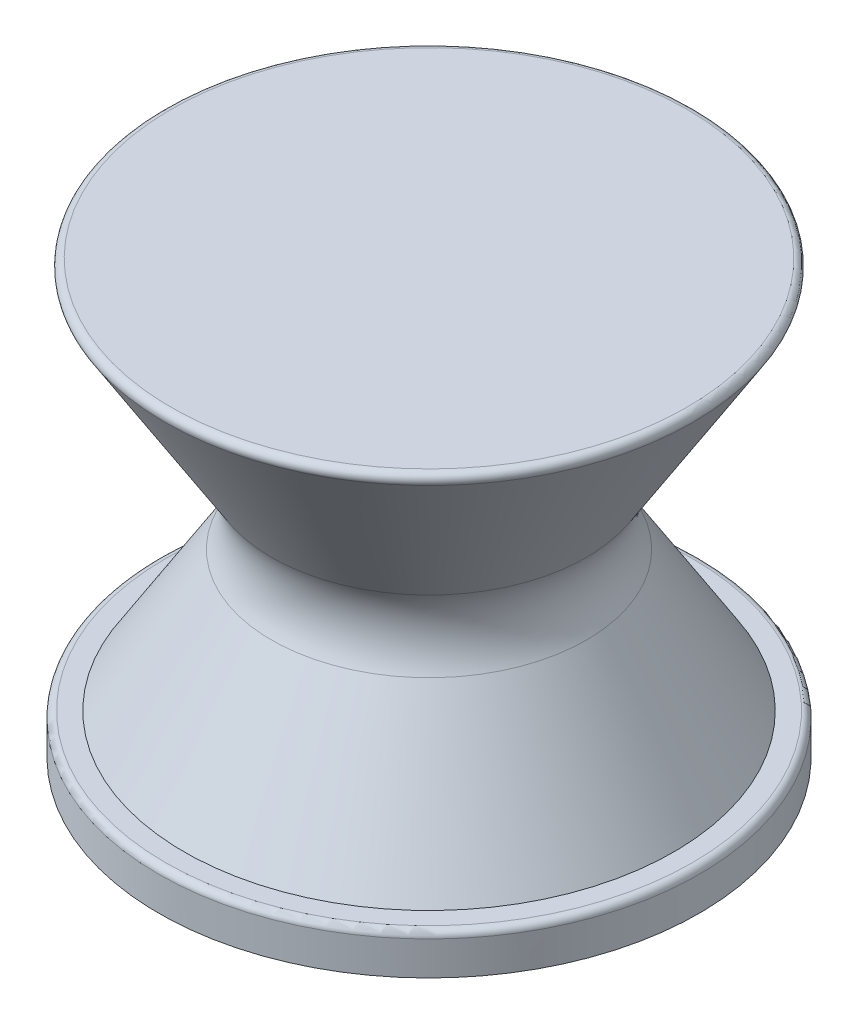
SolidWorks part; units mm, degrees
ref_plane "Front Plane" through (0, 0, 0) normal (0, 0, 1) x (1, 0, 0)
ref_plane "Top Plane" through (0, 0, 0) normal (0, 1, 0) x (1, 0, 0)
ref_plane "Right Plane" through (0, 0, 0) normal (1, 0, 0) x (0, 0, -1)
sketch "Sketch1" plane through (0, 0, 0) normal (1, 0, 0) x (0, 0, -1)
  line L0 (0, 0) -> (0, 32)
  line L1 (0, 32) -> (20, 32)
  line L2 (20, 32) -> (10, 16)
  line L3 (10, 16) -> (20, 0)
  line L4 (20, 0) -> (0, 0)
  line L5 (0, 16) -> (10, 16) construction
  line L6 (20, 32) -> (20, 29)
  line L7 (20, 29) -> (18.125, 29)
  line L8 (20, 0) -> (20, 3)
  line L9 (20, 3) -> (18.125, 3)
  line L10 (18.125, 29) -> (18.125, 3) construction
  dimension "D1" = 32
  dimension "D2" = 20
  dimension "D3" = 10
  dimension "D4" = 3
revolve "Revolve1" add sketch "Sketch1" angle 360 about L0
fillet "Fillet1" radius 5 1 edges at (0, 16, -10)
fillet "Fillet2" radius 0.5 1 edges at (0, 32, -20)
fillet "Fillet3" radius 0.5 1 edges at (0, 3, -20)
